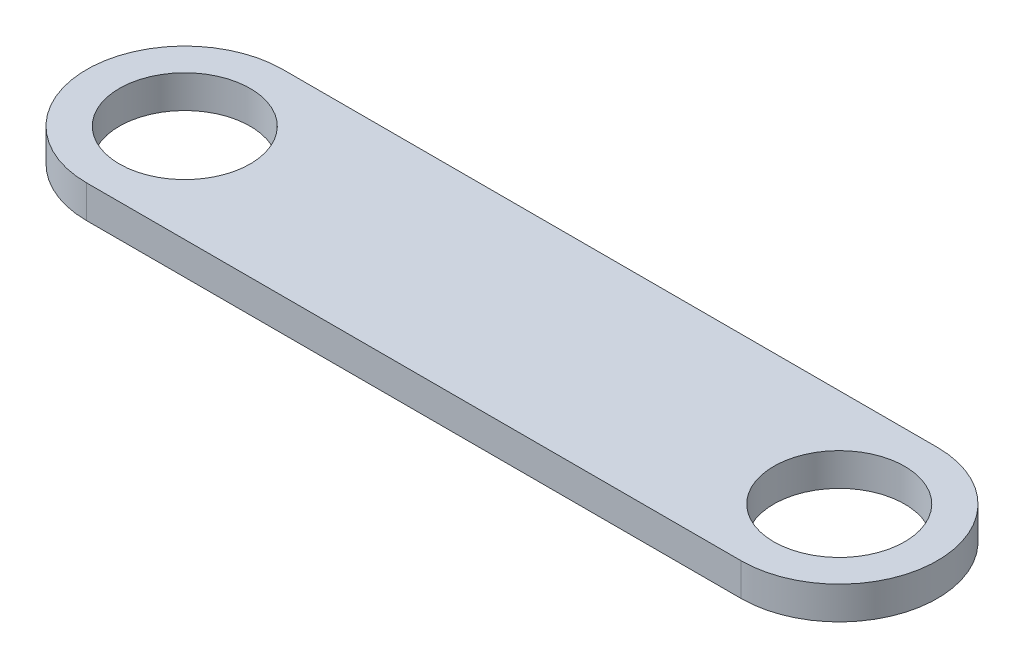
SolidWorks part; units mm, degrees
ref_plane "Front Plane" through (0, 0, 0) normal (0, 0, 1) x (1, 0, 0)
ref_plane "Top Plane" through (0, 0, 0) normal (0, 1, 0) x (1, 0, 0)
ref_plane "Right Plane" through (0, 0, 0) normal (1, 0, 0) x (0, 0, -1)
sketch "Sketch1" plane through (0, 0, 0) normal (0, 1, 0) x (1, 0, 0)
  line L0 (0, 0) -> (100, 0) construction
  line L1 (0, 15) -> (100, 15)
  line L2 (0, -15) -> (100, -15)
  circle A0 centre (0, 0) radius 5
  circle A1 centre (100, 0) radius 5
  arc A2 (0, 15) -> (0, -15) centre (0, 0) ccw
  arc A3 (100, -15) -> (100, 15) centre (100, 0) ccw
  circle A4 centre (0, 0) radius 10
  circle A5 centre (100, 0) radius 10
  circle A7 centre (0, 0) radius 15 construction
  circle A8 centre (100, 0) radius 15 construction
  point P6 (115, 0)
  point P17 (0, 0)
  point P18 (115.2022, 15)
  point P19 (0, 0)
  point P20 (0, 0)
  point P21 (15, 0)
  dimension "D2" = 10
  dimension "D1" = 100
  dimension "D3" = 10
  dimension "D4" = 10
  dimension "D5" = 5
extrude "Boss-Extrude1" add sketch "Sketch1" along normal blind 5 contours L2 A3 L1 A2 A5 A4
